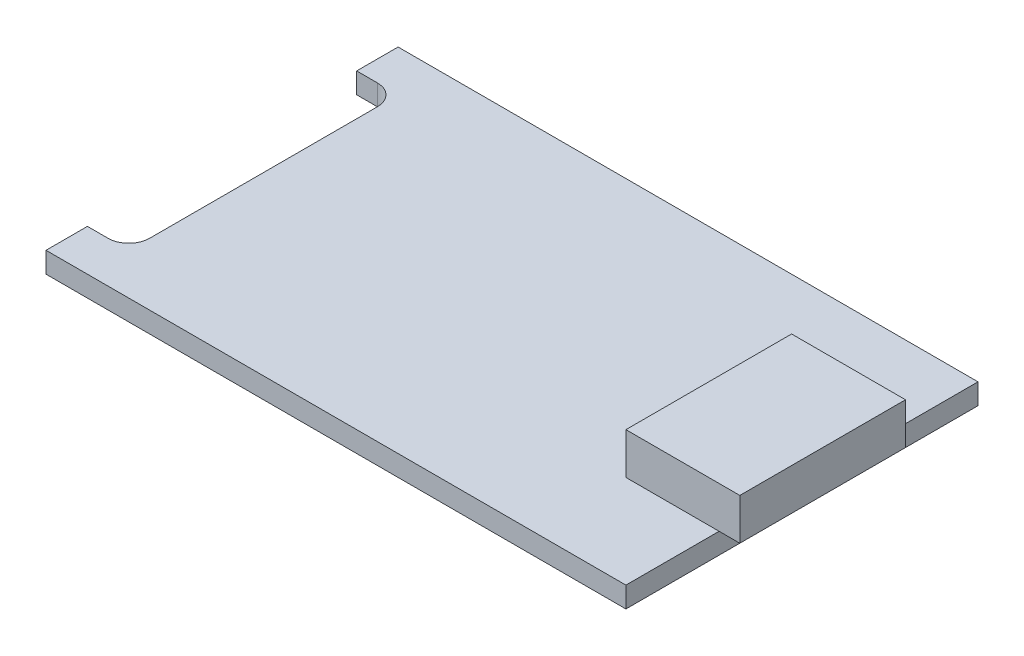
SolidWorks part; units mm, degrees
ref_plane "Front Plane" through (0, 0, 0) normal (0, 0, 1) x (1, 0, 0)
ref_plane "Top Plane" through (0, 0, 0) normal (0, 1, 0) x (1, 0, 0)
ref_plane "Right Plane" through (0, 0, 0) normal (1, 0, 0) x (0, 0, -1)
sketch "Sketch1" plane through (0, 0, 0) normal (0, 1, 0) x (1, 0, 0)
  line L1 (-14, -8.5) -> (14, -8.5)
  line L2 (-14, -8.5) -> (-14, 8.5)
  line L3 (-14, 8.5) -> (14, 8.5)
  line L4 (14, -8.5) -> (14, 8.5)
  point P4 (0, -8.5)
  point P6 (14, 0)
  dimension "D1" = 17
  dimension "D2" = 28
extrude "Boss-Extrude1" add sketch "Sketch1" along normal blind 1
sketch "Sketch2" plane through (0, 1, 0) normal (0, 1, 0) x (1, 0, 0)
  line L0 (14, -8.5) -> (14, 8.5) construction
  line L1 (15, 4) -> (9.5, 4)
  line L2 (15, 4) -> (15, -4)
  line L3 (15, -4) -> (9.5, -4)
  line L4 (9.5, 4) -> (9.5, -4)
  point P4 (15, 0)
  point P7 (14, 0)
  dimension "D1" = 1
  dimension "D2" = 5.5
  dimension "D3" = 8
extrude "Boss-Extrude2" add sketch "Sketch2" along normal blind 2
sketch "Sketch3" plane through (0, 1, 0) normal (0, 1, 0) x (1, 0, 0)
  line L0 (-14, 8.5) -> (-14, -8.5) construction
  line L1 (-14, 6.5) -> (-12, 6.5)
  line L2 (-14, 6.5) -> (-14, -6.5)
  line L3 (-14, -6.5) -> (-12, -6.5)
  line L4 (-12, 6.5) -> (-12, -6.5)
  line L5 (-14, -8.5) -> (14, -8.5) construction
  line L6 (14, 8.5) -> (-14, 8.5) construction
  dimension "D1" = 2
  dimension "D2" = 2
  dimension "D3" = 2
extrude "Cut-Extrude1" cut sketch "Sketch3" against normal through all
fillet "Fillet1" radius 1 2 edges at (-12, 0.5, 6.5) (-12, 0.5, -6.5)
